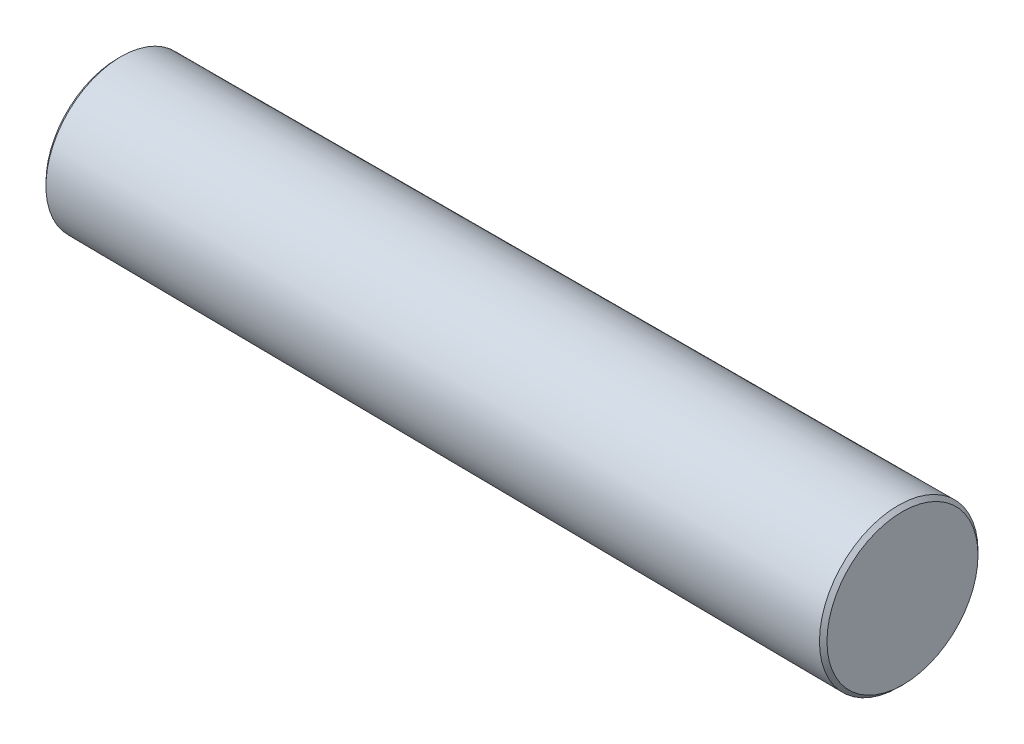
SolidWorks part; units mm, degrees
ref_plane "Front Plane" through (0, 0, 0) normal (0, 0, 1) x (1, 0, 0)
ref_plane "Top Plane" through (0, 0, 0) normal (0, 1, 0) x (1, 0, 0)
ref_plane "Right Plane" through (0, 0, 0) normal (1, 0, 0) x (0, 0, -1)
sketch "Sketch3" plane through (0, 0, 0) normal (0, 1, 0) x (1, 0, 0)
  line L0 (-10.5, 0) -> (10.5, -0.1013)
  line L2 (-10.5, 0) -> (-10.5, 2)
  line L3 (-10.5, 2) -> (10.5, 2)
  line L4 (10.5, -0.1013) -> (10.5, 2)
  line L5 (-0.4009, -0.0487) -> (0, 0) construction
  line L6 (0, 0) -> (0.4341, -0.0527) construction
  point P0 (0, 0)
  dimension "D1" = 10.5
  dimension "D2" = 21
  dimension "D3" = 2
revolve "Revolve1" add sketch "Sketch3" angle 360 about L0
chamfer "Chamfer10" distance 0.1 angle 45 2 edges at (10.4797, 0, 2.2025) (-10.5193, 0, 1.9999)
